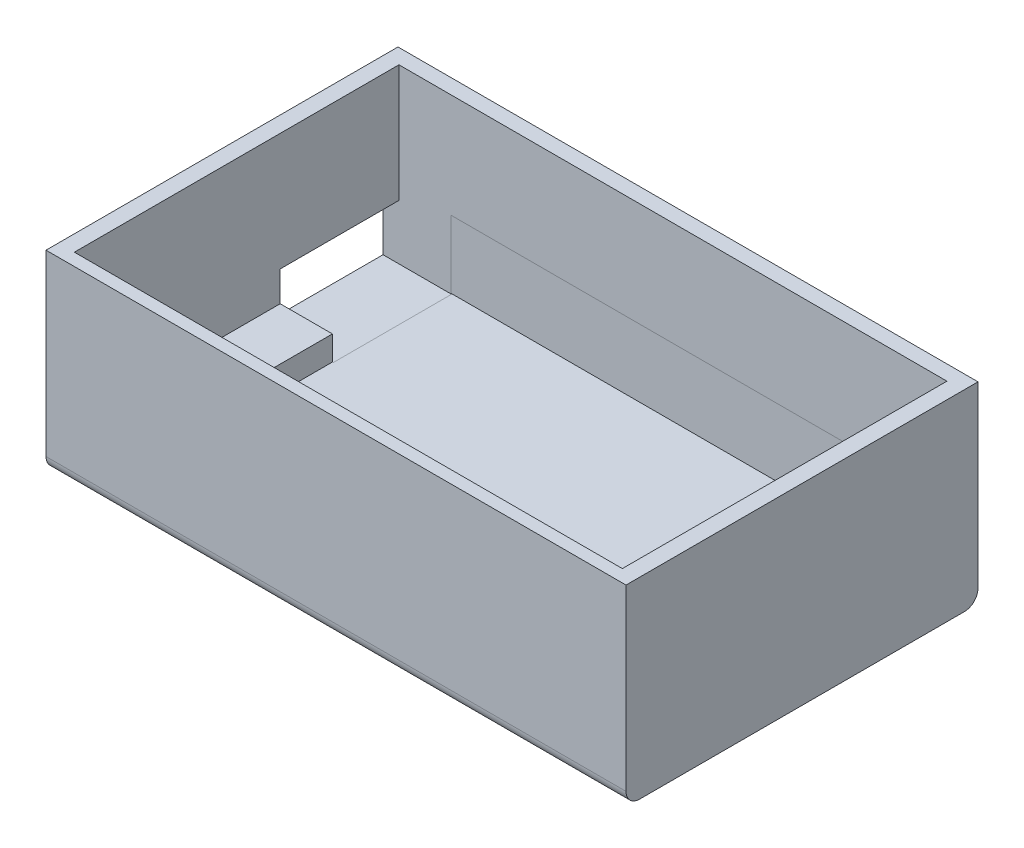
SolidWorks part; units mm, degrees
ref_plane "Front Plane" through (0, 0, 0) normal (0, 0, 1) x (1, 0, 0)
ref_plane "Top Plane" through (0, 0, 0) normal (0, 1, 0) x (1, 0, 0)
ref_plane "Right Plane" through (0, 0, 0) normal (1, 0, 0) x (0, 0, -1)
sketch "Sketch1" plane through (0, 0, 0) normal (0, 1, 0) x (1, 0, 0)
  line L13 (-42.525, 46.2472) -> (66.2991, 46.2472)
  line L14 (-42.525, 46.2472) -> (-42.525, -19.7928)
  line L15 (-42.525, -19.7928) -> (66.2991, -19.7928)
  line L16 (66.2991, 46.2472) -> (66.2991, -19.7928)
extrude "Boss-Extrude4" add sketch "Sketch1" along normal blind 3.81
sketch "Sketch5" plane through (0, 3.81, 0) normal (0, 1, 0) x (1, 0, 0)
  line L0 (-29.736, 43.4503) -> (63.2788, 43.4503)
  line L1 (-29.736, 43.4503) -> (-29.736, -17.4589)
  line L2 (-29.736, -17.4589) -> (63.2788, -17.4589)
  line L3 (63.2788, 43.4503) -> (63.2788, -17.4589)
  line L4 (58.7748, 38.8042) -> (31.165, 38.8042)
  line L5 (58.7748, 38.8042) -> (58.7748, -14.4139)
  line L6 (58.7748, -14.4139) -> (31.165, -14.4139)
  line L7 (31.165, 38.8042) -> (31.165, -14.4139)
  line L8 (-26.1373, 25.8245) -> (27.2027, 25.8245)
  line L9 (-26.1373, 25.8245) -> (-26.1373, -0.8455)
  line L10 (-26.1373, -0.8455) -> (27.2027, -0.8455)
  line L11 (27.2027, 25.8245) -> (27.2027, -0.8455)
  line L13 (-42.525, 46.2472) -> (66.2991, 46.2472)
  line L14 (-42.525, 46.2472) -> (-42.525, -19.7928)
  line L15 (-42.525, -19.7928) -> (66.2991, -19.7928)
  line L16 (66.2991, 46.2472) -> (66.2991, -19.7928)
extrude "Boss-Extrude5" add sketch "Sketch5" along normal blind 12.7 contours L1 L2 L3 L0 | L14 L15 L16 L13
sketch "Sketch6" plane through (-42.525, 0, 0) normal (-1, 0, 0) x (0, 0, 1)
  line L1 (-43.4402, 14.0343) -> (-21.1557, 14.0343)
  line L2 (-43.4402, 14.0343) -> (-43.4402, 3.7136)
  line L3 (-43.4402, 3.7136) -> (-21.1557, 3.7136)
  line L4 (-21.1557, 14.0343) -> (-21.1557, 3.7136)
extrude "Cut-Extrude2" cut sketch "Sketch6" against normal blind 12.954 contours L1 L4 L3 L2
fillet "Fillet2" radius 2.54 1 edges at (11.887, 0, 19.7928)
fillet "Fillet3" radius 2.54 1 edges at (11.887, 0, -46.2472)
sketch "Sketch8" plane through (0, 16.51, 0) normal (0, 1, 0) x (1, 0, 0)
  line L2 (-29.571, 43.4402) -> (-39.5354, 43.4402)
  line L3 (-29.571, 43.4402) -> (-29.571, -17.4589)
  line L4 (-29.571, -17.4589) -> (-39.5354, -17.4589)
  line L5 (-39.5354, 43.4402) -> (-39.5354, -17.4589)
  point P0 (0, 0)
extrude "Cut-Extrude4" cut sketch "Sketch8" against normal blind 8.128
sketch "Sketch11" plane through (0, 16.51, 0) normal (0, 1, 0) x (1, 0, 0)
  line L1 (66.2991, -19.7928) -> (-42.525, -19.7928)
  line L2 (66.2991, -19.7928) -> (66.2991, 46.2472)
  line L3 (66.2991, 46.2472) -> (-42.525, 46.2472)
  line L4 (-42.525, -19.7928) -> (-42.525, 46.2472)
  line L5 (-39.5354, 43.4402) -> (63.2788, 43.4402)
  line L6 (-39.5354, 43.4402) -> (-39.5354, -17.4589)
  line L7 (-39.5354, -17.4589) -> (63.2788, -17.4589)
  line L8 (63.2788, 43.4402) -> (63.2788, -17.4589)
extrude "Boss-Extrude6" add sketch "Sketch11" along normal blind 19.558
